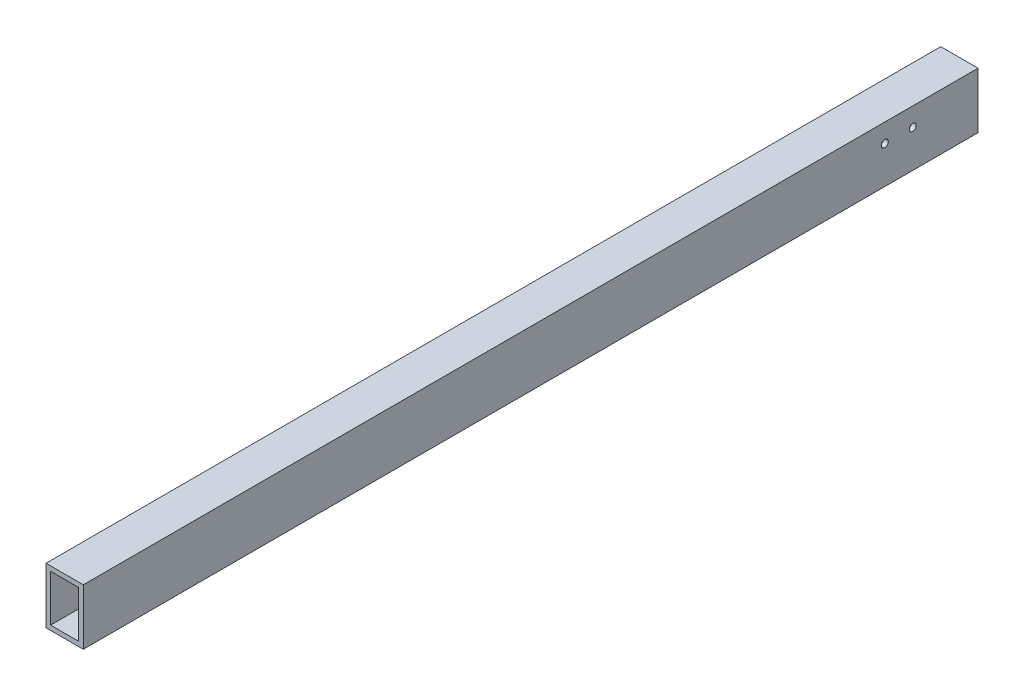
SolidWorks part; units mm, degrees
material "6063-T1"
ref_plane "Front Plane" through (0, 0, 0) normal (0, 0, 1) x (1, 0, 0)
ref_plane "Top Plane" through (0, 0, 0) normal (0, 1, 0) x (1, 0, 0)
ref_plane "Right Plane" through (0, 0, 0) normal (1, 0, 0) x (0, 0, -1)
sketch "Sketch1" plane through (0, 0, 0) normal (0, 0, 1) x (1, 0, 0)
  line L1 (-12.7, 19.05) -> (12.7, 19.05)
  line L2 (-12.7, 19.05) -> (-12.7, -19.05)
  line L3 (-12.7, -19.05) -> (12.7, -19.05)
  line L4 (12.7, 19.05) -> (12.7, -19.05)
  line L5 (-12.7, 19.05) -> (12.7, -19.05) construction
  line L6 (-12.7, -19.05) -> (12.7, 19.05) construction
  point P0 (0, 0)
  dimension "D1" = 25.4
  dimension "D2" = 38.1
extrude "Boss-Extrude1" add sketch "Sketch1" along normal blind 609.6
shell "Shell1" thickness 3.175
sketch "Sketch2" plane through (12.7, 0, 0) normal (1, 0, 0) x (0, 0, -1)
  line L0 (0, -19.05) -> (0, 19.05) construction
  line L1 (-609.6, -19.05) -> (0, -19.05) construction
  circle A0 centre (-44.45, 6.35) radius 2.3812
  circle A1 centre (-63.5, 6.35) radius 2.3812
  point P6 (-61.2443, 0)
  point P7 (0, 0)
  dimension "D2" = 4.7625
  dimension "D5" = 4.7625
  dimension "D1" = 44.45
  dimension "D3" = 25.4
  dimension "D4" = 19.05
  dimension "D6" = 25.4
extrude "Cut-Extrude1" cut sketch "Sketch2" against normal through all
